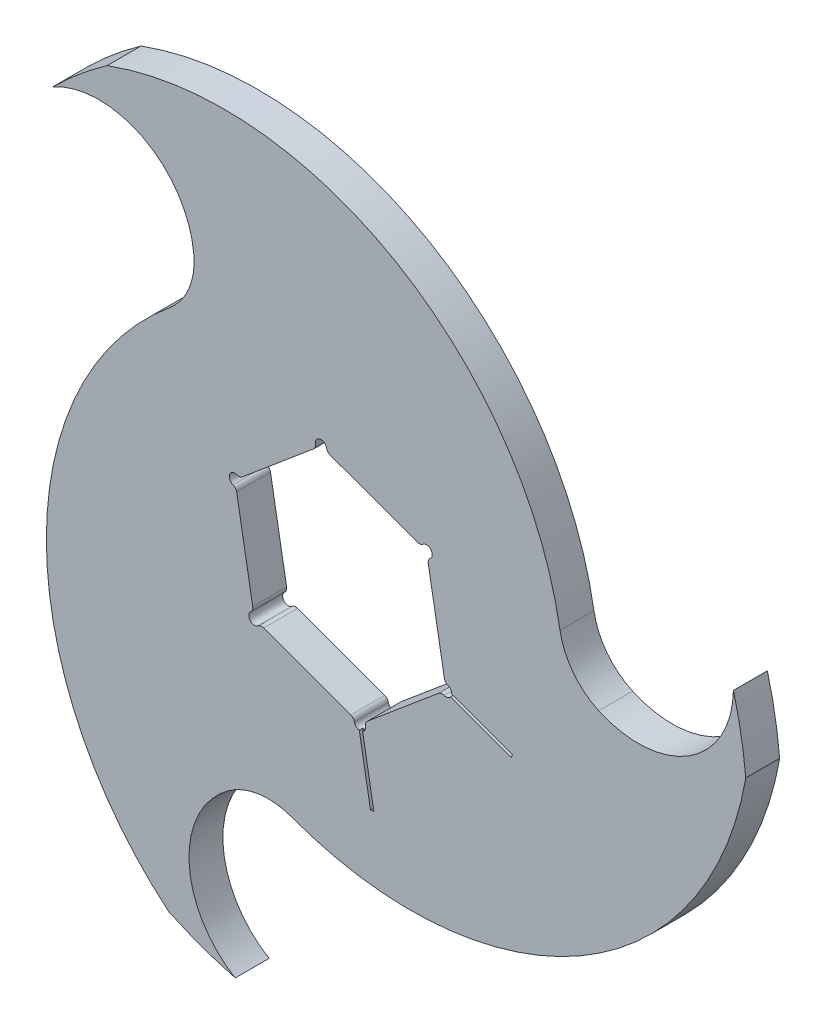
SolidWorks part; units mm, degrees
ref_plane "Front Plane" through (0, 0, 0) normal (0, 0, 1) x (1, 0, 0)
ref_plane "Top Plane" through (0, 0, 0) normal (0, 1, 0) x (1, 0, 0)
ref_plane "Right Plane" through (0, 0, 0) normal (1, 0, 0) x (0, 0, -1)
sketch "Sketch1" plane through (0, 0, 0) normal (0, 0, 1) x (1, 0, 0)
  line L6 (-151.6909, 0) -> (151.6909, 0) construction
  line L7 (0, 0) -> (0, 69.2266) construction
  line L8 (0, 0) -> (-2.8773, 16.3182) construction
  line L9 (-2.8773, 16.3182) -> (-3.5157, 15.7826) construction
  line L10 (-3.983, 15.3904) -> (-14.465, 6.595)
  line L11 (-15.32, 4.2458) -> (-12.944, -9.2295)
  line L12 (-11.337, -11.1446) -> (1.521, -15.8246)
  line L13 (3.983, -15.3904) -> (14.465, -6.595)
  line L14 (15.32, -4.2458) -> (12.944, 9.2295)
  line L15 (11.337, 11.1446) -> (-1.521, 15.8246)
  line L16 (-2.8773, 16.3182) -> (-2.0943, 16.0332) construction
  arc A2 (32.823, 7.1564) -> (-34.4264, 49.1408) centre (-17.1264, 2.0002) ccw
  arc A3 (-34.4264, 49.1408) -> (-42.4264, 42.4264) centre (0, 0) ccw
  arc A4 (-42.4264, 42.4264) -> (-22.6091, 24.8474) centre (-35.6099, 30.151) cw
  arc A5 (-10.2139, -32.0037) -> (59.7704, 5.2438) centre (10.2954, 13.8318) ccw
  arc A6 (59.7704, 5.2438) -> (57.9555, 15.5291) centre (0, 0) ccw
  arc A7 (57.9555, 15.5291) -> (32.823, 7.1564) centre (43.9165, 15.7636) cw
  arc A8 (-22.6091, 24.8474) -> (-25.344, -54.3846) centre (6.8309, -15.832) ccw
  arc A9 (-25.344, -54.3846) -> (-15.5291, -57.9555) centre (0, 0) ccw
  arc A10 (-15.5291, -57.9555) -> (-10.2139, -32.0037) centre (-8.3066, -45.9146) cw
  circle A11 centre (0, 0) radius 60 construction
  circle A12 centre (0, 0) radius 14.35 construction
  arc A13 (-2.0567, 16.4629) -> (-3.698, 16.1735) centre (-2.8773, 16.3182) ccw
  arc A14 (-3.698, 16.1735) -> (-3.983, 15.3904) centre (-4.5187, 16.0288) cw
  arc A15 (-1.521, 15.8246) -> (-2.0567, 16.4629) centre (-1.236, 16.6076) cw
  arc A16 (12.1577, 11.2893) -> (11.337, 11.1446) centre (11.622, 11.9277) cw
  arc A17 (13.229, 10.0126) -> (12.1577, 11.2893) centre (12.6933, 10.651) ccw
  arc A18 (12.944, 9.2295) -> (13.229, 10.0126) centre (13.7646, 9.3742) cw
  arc A19 (15.8557, -4.8842) -> (15.32, -4.2458) centre (16.1407, -4.1011) cw
  arc A20 (15.2856, -6.4503) -> (15.8557, -4.8842) centre (15.5707, -5.6673) ccw
  arc A21 (14.465, -6.595) -> (15.2856, -6.4503) centre (15.0006, -7.2334) cw
  arc A22 (3.698, -16.1735) -> (3.983, -15.3904) centre (4.5187, -16.0288) cw
  arc A23 (2.0567, -16.4629) -> (3.698, -16.1735) centre (2.8773, -16.3182) ccw
  arc A24 (1.521, -15.8246) -> (2.0567, -16.4629) centre (1.236, -16.6076) cw
  arc A25 (-12.1577, -11.2893) -> (-11.337, -11.1446) centre (-11.622, -11.9277) cw
  arc A26 (-13.229, -10.0126) -> (-12.1577, -11.2893) centre (-12.6933, -10.651) ccw
  arc A27 (-12.944, -9.2295) -> (-13.229, -10.0126) centre (-13.7646, -9.3742) cw
  arc A28 (-15.8557, 4.8842) -> (-15.32, 4.2458) centre (-16.1407, 4.1011) cw
  arc A29 (-15.2856, 6.4503) -> (-15.8557, 4.8842) centre (-15.5707, 5.6673) ccw
  arc A30 (-14.465, 6.595) -> (-15.2856, 6.4503) centre (-15.0006, 7.2334) cw
  point P22 (0, 0)
  point P29 (0, 0)
  point P74 (0, 0)
  dimension "D3" = 1.6667
  dimension "D2" = 28.7
  dimension "D6" = 0.8333
  dimension "D7" = 0.8333
  dimension "D1" = 10
extrude "Boss-Extrude1" add sketch "Sketch1" along normal blind 5
fillet "Fillet1" radius 10 3 edges at (-10.2139, -32.0037, 2.5) (-22.6091, 24.8474, 2.5) (32.823, 7.1564, 2.5)
sketch "Sketch2" plane through (0, 0, 5) normal (0, 0, 1) x (1, 0, 0)
  line L0 (0, 0) -> (3.022, -17.1389) construction
  line L6 (3.022, -17.1389) -> (2.9352, -16.6465) construction
  line L8 (2.689, -16.6899) -> (3.1814, -16.6031)
  line L9 (2.689, -16.6899) -> (4.4255, -26.538)
  line L10 (3.1814, -16.6031) -> (4.9179, -26.4512)
  line L11 (4.4255, -26.538) -> (4.9179, -26.4512)
  line L12 (15.7984, -6.0162) -> (15.9694, -5.5463)
  line L13 (15.7984, -6.0162) -> (25.1953, -9.4364)
  line L14 (15.9694, -5.5463) -> (25.3663, -8.9665)
  line L15 (25.1953, -9.4364) -> (25.3663, -8.9665)
  arc A0 (2.0567, -16.4629) -> (3.698, -16.1735) centre (2.8773, -16.3182) ccw construction
  point P10 (2.9352, -16.6465)
  point P19 (0, 0)
  dimension "D1" = 0.5
  dimension "D2" = 0.5
  dimension "D3" = 10
  dimension "D4" = 2
extrude "Cut-Extrude1" cut sketch "Sketch2" against normal blind 0.5
